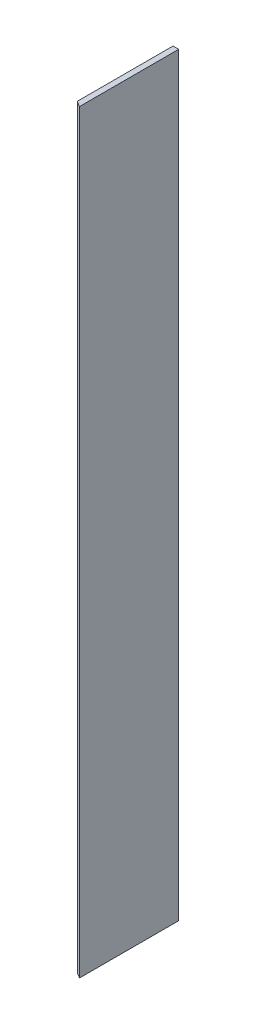
SolidWorks part; units mm, degrees
ref_plane "Спереди" through (0, 0, 0) normal (0, 0, 1) x (1, 0, 0)
ref_plane "Сверху" through (0, 0, 0) normal (0, 1, 0) x (1, 0, 0)
ref_plane "Справа" through (0, 0, 0) normal (1, 0, 0) x (0, 0, -1)
sketch "Эскиз1" plane through (0, 0, 0) normal (0, 1, 0) x (1, 0, 0)
  line L1 (1, 0) -> (5, 0)
  line L2 (1, 0) -> (1, -67.636)
  line L3 (1, -67.636) -> (5, -70.0688)
  line L4 (5, 0) -> (5, -70.0688)
  line L6 (5, -70.2138) -> (5, 227.4589) construction
  dimension "D1" = 4
extrude "Вытянуть1" add sketch "Эскиз1" along normal blind 533
